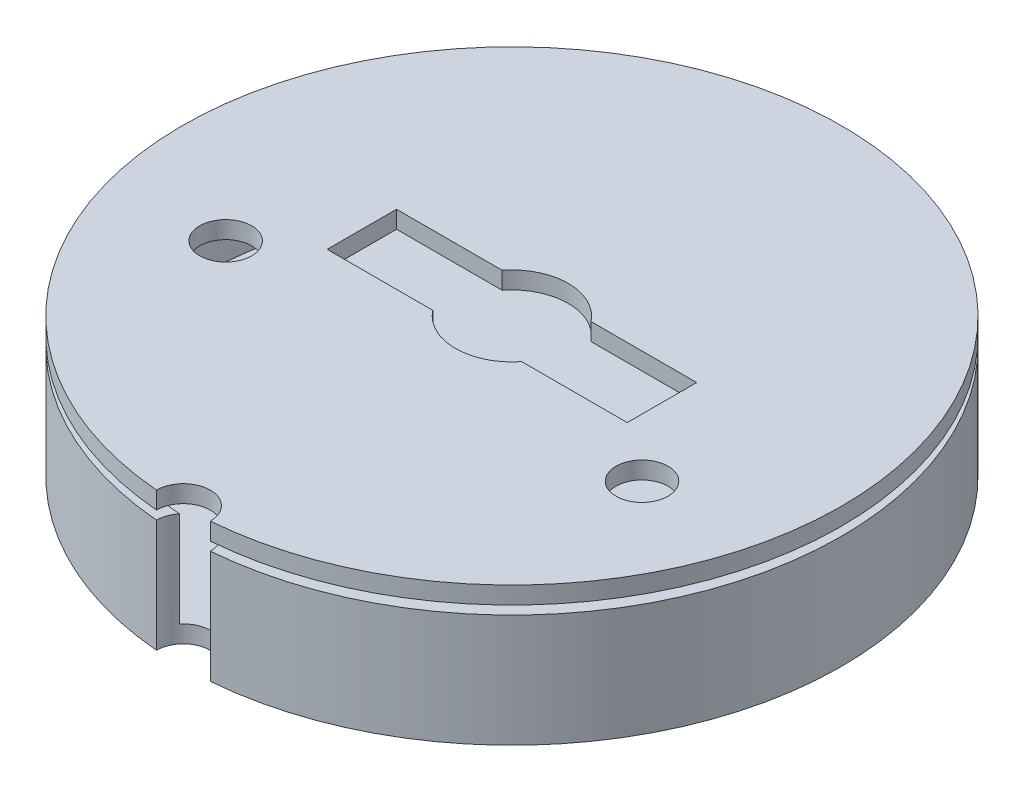
SolidWorks part; units mm, degrees
ref_plane "Front Plane" through (0, 0, 0) normal (0, 0, 1) x (1, 0, 0)
ref_plane "Top Plane" through (0, 0, 0) normal (0, 1, 0) x (1, 0, 0)
ref_plane "Right Plane" through (0, 0, 0) normal (1, 0, 0) x (0, 0, -1)
sketch "Sketch1" plane through (0, 0, 0) normal (0, 1, 0) x (1, 0, 0)
  line L2 (0, 0) -> (0, -44.1621) construction
  arc A0 (3.937, -48.0991) -> (-3.937, -48.0991) centre (0, 0) ccw
  circle A2 centre (0, 0) radius 5.588
  arc A3 (3.937, -48.0991) -> (-3.937, -48.0991) centre (0, -48.0991) ccw
  dimension "D1" = 11.176
  dimension "D2" = 96.52
  dimension "D3" = 7.874
extrude "Boss-Extrude1" add sketch "Sketch1" along normal blind 20.32
sketch "Sketch2" plane through (0, 0, 0) normal (0, 1, 0) x (1, 0, 0)
  line L0 (0, 0) -> (0, 48.26) construction
  line L1 (-48.26, 0) -> (48.26, 0) construction
  line L2 (28.9804, 25.1221) -> (47.5785, 25.1221)
  line L4 (47.5785, -16.6643) -> (47.5785, 25.1221)
  line L5 (-28.9804, 25.1221) -> (-54.2576, 25.1221)
  line L7 (-54.2576, -16.6643) -> (-54.2576, 25.1221)
  line L8 (-28.9804, -11.9619) -> (28.9804, -11.9619)
  line L9 (47.5785, -16.6643) -> (47.5785, -51.6601)
  line L10 (47.5785, -51.6601) -> (-54.2576, -51.6601)
  line L11 (-54.2576, -51.6601) -> (-54.2576, -16.6643)
  circle A0 centre (0, 0) radius 48.26 construction
  circle A1 centre (0, 29.718) radius 18.542 construction
  arc A2 (28.9804, 25.1221) -> (28.9804, -11.9619) centre (28.9804, 6.5801) ccw
  arc A3 (-28.9804, 25.1221) -> (-28.9804, -11.9619) centre (-28.9804, 6.5801) cw
  dimension "D1" = 37.084
  dimension "D2" = 37.084
sketch "Sketch4" plane through (0, 0, 0) normal (0, 1, 0) x (1, 0, 0)
  line L0 (-17.272, 29.718) -> (-17.272, 49.4663)
  line L1 (17.272, 29.718) -> (17.272, 49.4663)
  line L2 (17.272, 49.4663) -> (-17.272, 49.4663)
  arc A0 (-17.272, 29.718) -> (17.272, 29.718) centre (0, 29.718) ccw
  circle A1 centre (0, 29.718) radius 18.542 construction
  dimension "D1" = 1.27
extrude "Cut-Extrude3" [suppressed] cut sketch "Sketch2" along normal blind 10.16
extrude "Cut-Extrude4" [suppressed] cut sketch "Sketch4" along normal blind 10.16 contours L2 L0 A0 L1
sketch "Sketch5" plane through (0, 0, 0) normal (0, 1, 0) x (1, 0, 0)
  circle A0 centre (0, 0) radius 8.255
  dimension "D1" = 16.51
extrude "Cut-Extrude5" cut sketch "Sketch5" along normal blind 47.498 from offset 2.54
sketch "Sketch6" plane through (0, 0, 0) normal (0, 1, 0) x (1, 0, 0)
  circle A0 centre (0, 0) radius 45.72
  arc A1 (3.937, -48.0991) -> (-3.937, -48.0991) centre (0, 0) ccw construction
  circle A2 centre (0, 0) radius 8.1721
  dimension "D1" = 2.54
  dimension "D2" = 16.3441
extrude "Cut-Extrude7" cut sketch "Sketch6" against normal blind 15.24 from offset 17.78 contours A0
sketch "Sketch7" plane through (0, 0, 0) normal (0, 1, 0) x (1, 0, 0)
  line L1 (-21.971, -5.08) -> (21.971, -5.08)
  line L2 (-21.971, -5.08) -> (-21.971, 5.08)
  line L3 (-21.971, 5.08) -> (21.971, 5.08)
  line L4 (21.971, -5.08) -> (21.971, 5.08)
  line L5 (-21.971, -5.08) -> (21.971, 5.08) construction
  line L6 (-21.971, 5.08) -> (21.971, -5.08) construction
  point P0 (0, 0)
  dimension "D1" = 43.942
  dimension "D2" = 10.16
extrude "Cut-Extrude8" cut sketch "Sketch7" along normal blind 28.448 from offset 10.16
sketch "Sketch8" plane through (0, 0, 0) normal (1, 0, 0) x (0, 0, -1)
  line L0 (-52.8354, 17.78) -> (55.7377, 17.78)
  line L1 (55.7377, 17.78) -> (55.7377, 16.51)
  line L2 (55.7377, 16.51) -> (-52.8354, 16.51)
  line L3 (-52.8354, 16.51) -> (-52.8354, 17.78)
  line L5 (48.26, 20.32) -> (-48.0991, 20.32) construction
  dimension "D1" = 2.54
  dimension "D2" = 1.27
extrude "Cut-Extrude9" cut sketch "Sketch8" against normal blind 70.612 and the other way blind 72.898
sketch "Sketch9" plane through (0, 0, 0) normal (0, 1, 0) x (1, 0, 0)
  line L0 (-48.26, 0) -> (48.26, 0) construction
  line L1 (0, 0) -> (0, -51.6601) construction
  line L2 (47.5785, -51.6601) -> (-54.2576, -51.6601) construction
  circle A0 centre (-30.48, -11.43) radius 3.81
  circle A1 centre (30.48, -11.43) radius 3.81
  dimension "D1" = 7.62
  dimension "D2" = 11.43
  dimension "D3" = 30.48
extrude "Cut-Extrude10" cut sketch "Sketch9" along normal blind 39.37
split "Split1" bodies to split 114 115 resulting bodies 112 113
